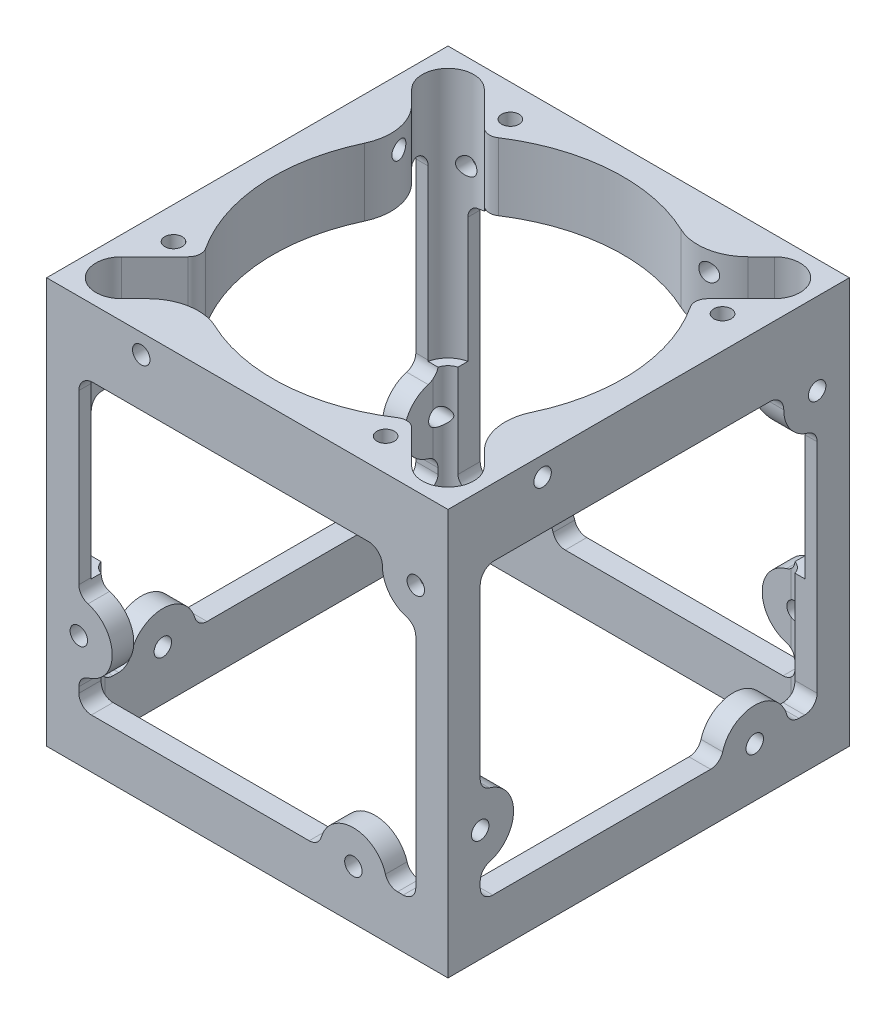
SolidWorks part; units mm, degrees
ref_plane "Front" through (0, 0, 0) normal (0, 0, 1) x (1, 0, 0)
ref_plane "Top" through (0, 0, 0) normal (0, 1, 0) x (1, 0, 0)
ref_plane "Right" through (0, 0, 0) normal (1, 0, 0) x (0, 0, -1)
other "Center of Mass"
sketch "Sketch1" plane through (0, 0, 0) normal (0, 1, 0) x (1, 0, 0)
  line L1 (-25.4, 25.4) -> (25.4, 25.4)
  line L2 (-25.4, 25.4) -> (-25.4, -25.4)
  line L3 (-25.4, -25.4) -> (25.4, -25.4)
  line L4 (25.4, 25.4) -> (25.4, -25.4)
  line L5 (-25.4, 25.4) -> (25.4, -25.4) construction
  line L6 (-25.4, -25.4) -> (25.4, 25.4) construction
  point P0 (0, 0)
  dimension "D1" = 50.8
  dimension "D2" = 50.8
extrude "Boss-Extrude1" add sketch "Sketch1" along normal blind 47.5488
sketch "Sketch2" plane through (0, 0, 0) normal (0, -1, 0) x (-1, 0, 0)
  line L1 (20.7645, -22.6695) -> (-20.7645, -22.6695)
  line L2 (22.6695, -20.7645) -> (22.6695, 20.7645)
  line L3 (20.7645, 22.6695) -> (-20.7645, 22.6695)
  line L4 (-22.6695, -20.7645) -> (-22.6695, 20.7645)
  line L5 (22.6695, -22.6695) -> (-22.6695, 22.6695) construction
  line L6 (22.6695, 22.6695) -> (-22.6695, -22.6695) construction
  arc A0 (-20.7645, 22.6695) -> (-22.6695, 20.7645) centre (-20.7645, 20.7645) ccw
  arc A1 (-22.6695, -20.7645) -> (-20.7645, -22.6695) centre (-20.7645, -20.7645) ccw
  arc A2 (20.7645, -22.6695) -> (22.6695, -20.7645) centre (20.7645, -20.7645) ccw
  arc A3 (20.7645, 22.6695) -> (22.6695, 20.7645) centre (20.7645, 20.7645) cw
  point P0 (0, 0)
  dimension "D3" = 1.905
  dimension "D1" = 45.339
  dimension "D2" = 45.339
extrude "Cut-Extrude1" cut sketch "Sketch2" against normal blind 33.02
sketch "Sketch4" plane through (0, 0, 0) normal (0, -1, 0) x (-1, 0, 0)
  line L0 (-22.1115, -22.1115) -> (-23.495, -23.495)
  line L3 (0, 0) -> (0, -4.5871)
  line L4 (-25.4, 0) -> (-22.6695, 0)
  line L5 (-25.4, -25.4) -> (-25.4, 25.4) construction
  line L6 (-22.6695, 20.7645) -> (-22.6695, -20.7645) construction
  line L8 (-23.495, -23.495) -> (23.495, -23.495)
  line L9 (-23.495, -23.495) -> (-23.495, 23.495)
  line L10 (-23.495, 23.495) -> (23.495, 23.495)
  line L11 (23.495, -23.495) -> (23.495, 23.495)
  line L12 (-23.495, -23.495) -> (23.495, 23.495) construction
  line L13 (-23.495, 23.495) -> (23.495, -23.495) construction
  arc A1 (-22.6695, -20.7645) -> (-20.7645, -22.6695) centre (-20.7645, -20.7645) ccw construction
  circle A2 centre (-23.495, -23.495) radius 1.1049
  circle A3 centre (23.495, -23.495) radius 1.1049
  circle A4 centre (-23.495, 23.495) radius 1.1049
  circle A5 centre (23.495, 23.495) radius 1.1049
  dimension "D2" = 2.2098
  dimension "D1" = 46.99
extrude "Cut-Extrude3" cut sketch "Sketch4" against normal blind 6.985 contours A3 | A5 | A4 | A2
sketch "Sketch5" plane through (0, 0, -25.4) normal (0, 0, -1) x (-1, 0, 0)
  line L0 (0, 0) -> (0, 47.5488)
  line L1 (-25.4, 0) -> (25.4, 0) construction
  line L2 (-25.4, 47.5488) -> (25.4, 47.5488) construction
  line L3 (0, 23.7744) -> (20.574, 23.7744)
  line L4 (0, 23.7744) -> (-20.574, 23.7744)
  line L5 (-23.7744, 47.5488) -> (23.7744, 47.5488)
  line L6 (-23.7744, 47.5488) -> (-23.7744, 0)
  line L7 (-23.7744, 0) -> (23.7744, 0)
  line L8 (23.7744, 47.5488) -> (23.7744, 0)
  line L9 (-23.7744, 47.5488) -> (23.7744, 0) construction
  line L10 (-23.7744, 0) -> (23.7744, 47.5488) construction
  circle A0 centre (-20.574, 23.7744) radius 0.5
  circle A1 centre (20.574, 23.7744) radius 0.5
  circle A2 centre (21.3233, 10.3505) radius 1.1049
  circle A3 centre (-13.4239, 2.4511) radius 1.1049
  circle A4 centre (-21.3233, 37.1983) radius 1.1049
  circle A5 centre (13.4239, 45.0977) radius 1.1049
  circle A6 centre (-21.3233, 10.3505) radius 1.1049
  circle A7 centre (-13.4239, 45.0977) radius 1.1049
  circle A8 centre (13.4239, 2.4511) radius 1.1049
  circle A9 centre (21.3233, 37.1983) radius 1.1049
  dimension "D1" = 1
  dimension "D2" = 1
  dimension "D3" = 2.2098
  dimension "D4" = 2.2098
  dimension "D5" = 2.2098
  dimension "D6" = 2.2098
  dimension "D7" = 20.574
  dimension "D8" = 20.574
extrude "Cut-Extrude5" cut sketch "Sketch5" against normal blind 6.985
sketch "Sketch6" plane through (-25.4, 0, 0) normal (-1, 0, 0) x (0, 0, 1)
  line L0 (0, 47.5488) -> (0, 0)
  line L1 (-25.4, 47.5488) -> (25.4, 47.5488) construction
  line L2 (-25.4, 0) -> (25.4, 0) construction
  line L3 (0, 0) -> (0, 47.5488)
  line L4 (0, 23.7744) -> (20.574, 23.7744)
  line L5 (0, 23.7744) -> (-20.574, 23.7744)
  line L6 (-23.7744, 47.5488) -> (23.7744, 47.5488)
  line L7 (-23.7744, 47.5488) -> (-23.7744, 0)
  line L8 (-23.7744, 0) -> (23.7744, 0)
  line L9 (23.7744, 47.5488) -> (23.7744, 0)
  line L10 (-23.7744, 47.5488) -> (23.7744, 0) construction
  line L11 (-23.7744, 0) -> (23.7744, 47.5488) construction
  circle A0 centre (-20.574, 23.7744) radius 0.5
  circle A1 centre (20.574, 23.7744) radius 0.5
  circle A2 centre (21.3233, 10.3505) radius 1.1049
  circle A3 centre (-13.4239, 2.4511) radius 1.1049
  circle A4 centre (-21.3233, 37.1983) radius 1.1049
  circle A5 centre (13.4239, 45.0977) radius 1.1049
  circle A6 centre (-21.3233, 10.3505) radius 1.1049
  circle A7 centre (-13.4239, 45.0977) radius 1.1049
  circle A8 centre (13.4239, 2.4511) radius 1.1049
  circle A9 centre (21.3233, 37.1983) radius 1.1049
  dimension "D1" = 1
  dimension "D2" = 2.2098
  dimension "D3" = 2.2098
  dimension "D4" = 20.574
  dimension "D5" = 20.574
extrude "Cut-Extrude6" cut sketch "Sketch6" against normal blind 6.985
sketch "Sketch7" plane through (0, 47.5488, 0) normal (0, 1, 0) x (1, 0, 0)
  line L0 (0, 25.4) -> (0, -25.4)
  line L1 (25.4, 25.4) -> (-25.4, 25.4) construction
  line L2 (-25.4, -25.4) -> (25.4, -25.4) construction
  line L3 (0, -23.7744) -> (0, 23.7744)
  line L4 (0, 0) -> (20.574, 0)
  line L5 (0, 0) -> (-20.574, 0)
  line L6 (-23.7744, 23.7744) -> (23.7744, 23.7744)
  line L7 (-23.7744, 23.7744) -> (-23.7744, -23.7744)
  line L8 (-23.7744, -23.7744) -> (23.7744, -23.7744)
  line L9 (23.7744, 23.7744) -> (23.7744, -23.7744)
  line L10 (-23.7744, 23.7744) -> (23.7744, -23.7744) construction
  line L11 (-23.7744, -23.7744) -> (23.7744, 23.7744) construction
  circle A0 centre (-20.574, 0) radius 0.5
  circle A1 centre (20.574, 0) radius 0.5
  circle A2 centre (21.3233, -13.4239) radius 1.1049
  circle A3 centre (-13.4239, -21.3233) radius 1.1049
  circle A4 centre (-21.3233, 13.4239) radius 1.1049
  circle A5 centre (13.4239, 21.3233) radius 1.1049
  circle A6 centre (-21.3233, -13.4239) radius 1.1049
  circle A7 centre (-13.4239, 21.3233) radius 1.1049
  circle A8 centre (13.4239, -21.3233) radius 1.1049
  circle A9 centre (21.3233, 13.4239) radius 1.1049
  dimension "D1" = 1
  dimension "D2" = 2.2098
  dimension "D3" = 2.2098
  dimension "D4" = 20.574
  dimension "D5" = 20.574
extrude "Cut-Extrude7" cut sketch "Sketch7" against normal blind 6.985
sketch "Sketch8" plane through (0, 0, 25.4) normal (0, 0, 1) x (1, 0, 0)
  line L0 (0, 47.5488) -> (0, 0)
  line L1 (-25.4, 47.5488) -> (25.4, 47.5488) construction
  line L2 (-25.4, 0) -> (25.4, 0) construction
  line L3 (0, 0) -> (0, 47.5488)
  line L4 (0, 23.7744) -> (20.574, 23.7744)
  line L5 (0, 23.7744) -> (-20.574, 23.7744)
  line L6 (-23.7744, 47.5488) -> (23.7744, 47.5488)
  line L7 (-23.7744, 47.5488) -> (-23.7744, 0)
  line L8 (-23.7744, 0) -> (23.7744, 0)
  line L9 (23.7744, 47.5488) -> (23.7744, 0)
  line L10 (-23.7744, 47.5488) -> (23.7744, 0) construction
  line L11 (-23.7744, 0) -> (23.7744, 47.5488) construction
  circle A0 centre (-20.574, 23.7744) radius 0.5
  circle A1 centre (20.574, 23.7744) radius 0.5
  circle A2 centre (21.3233, 10.3505) radius 1.1049
  circle A3 centre (-13.4239, 2.4511) radius 1.1049
  circle A4 centre (-21.3233, 37.1983) radius 1.1049
  circle A5 centre (13.4239, 45.0977) radius 1.1049
  circle A6 centre (-21.3233, 10.3505) radius 1.1049
  circle A7 centre (-13.4239, 45.0977) radius 1.1049
  circle A8 centre (13.4239, 2.4511) radius 1.1049
  circle A9 centre (21.3233, 37.1983) radius 1.1049
  dimension "D1" = 1
  dimension "D2" = 2.2098
  dimension "D3" = 2.2098
  dimension "D4" = 20.574
  dimension "D5" = 20.574
extrude "Cut-Extrude8" cut sketch "Sketch8" against normal blind 6.985 contours A6 | A7 | A9 | A8 | A1 | A0
sketch "Sketch9" plane through (25.4, 0, 0) normal (1, 0, 0) x (0, 0, -1)
  line L0 (0, 47.5488) -> (0, 0)
  line L1 (-25.4, 47.5488) -> (25.4, 47.5488) construction
  line L2 (-25.4, 0) -> (25.4, 0) construction
  line L3 (0, 0) -> (0, 47.5488)
  line L4 (0, 23.7744) -> (20.574, 23.7744)
  line L5 (0, 23.7744) -> (-20.574, 23.7744)
  line L6 (-23.7744, 47.5488) -> (23.7744, 47.5488)
  line L7 (-23.7744, 47.5488) -> (-23.7744, 0)
  line L8 (-23.7744, 0) -> (23.7744, 0)
  line L9 (23.7744, 47.5488) -> (23.7744, 0)
  line L10 (-23.7744, 47.5488) -> (23.7744, 0) construction
  line L11 (-23.7744, 0) -> (23.7744, 47.5488) construction
  circle A0 centre (-20.574, 23.7744) radius 0.5
  circle A1 centre (20.574, 23.7744) radius 0.5
  circle A2 centre (21.3233, 10.3505) radius 1.1049
  circle A3 centre (-13.4239, 2.4511) radius 1.1049
  circle A4 centre (-21.3233, 37.1983) radius 1.1049
  circle A5 centre (13.4239, 45.0977) radius 1.1049
  circle A6 centre (-21.3233, 10.3505) radius 1.1049
  circle A7 centre (-13.4239, 45.0977) radius 1.1049
  circle A8 centre (13.4239, 2.4511) radius 1.1049
  circle A9 centre (21.3233, 37.1983) radius 1.1049
  dimension "D1" = 1
  dimension "D2" = 2.2098
  dimension "D3" = 2.2098
  dimension "D4" = 20.574
  dimension "D5" = 20.574
extrude "Cut-Extrude9" cut sketch "Sketch9" against normal blind 6.985
sketch "Sketch10" plane through (-25.4, 0, 0) normal (-1, 0, 0) x (0, 0, 1)
  line L0 (0, 0) -> (0, 38.9989)
  line L1 (15.3201, 38.9989) -> (-19.5453, 38.9989)
  line L2 (0, 23.7744) -> (25.4, 23.7744)
  line L6 (25.4, 47.5488) -> (25.4, 0) construction
  line L8 (21.3233, 31.6065) -> (21.3233, 4.0386)
  line L9 (-25.4, 23.7744) -> (25.4, 23.7744)
  line L11 (19.7358, 2.4511) -> (19.0157, 2.4511)
  line L12 (7.8321, 2.4511) -> (-19.7358, 2.4511)
  line L13 (-21.3233, 11.4554) -> (-21.3233, 9.2456)
  line L14 (-21.3233, 4.0386) -> (-21.3233, 4.7587)
  line L15 (-21.3233, 15.9423) -> (-21.3233, 37.2209)
  line L19 (13.4239, 3.556) -> (13.4239, 1.3462)
  line L22 (0, 38.9989) -> (0, 0)
  arc A0 (17.098, 37.2142) -> (20.1694, 33.1336) centre (21.3233, 37.1983) ccw
  arc A1 (-20.1694, 6.2858) -> (-20.1694, 14.4152) centre (-21.3233, 10.3505) ccw
  arc A5 (20.1694, 33.1336) -> (21.3233, 31.6065) centre (19.7358, 31.6065) cw
  arc A6 (19.7358, 2.4511) -> (21.3233, 4.0386) centre (19.7358, 4.0386) ccw
  arc A7 (17.4886, 3.605) -> (9.3592, 3.605) centre (13.4239, 2.4511) ccw
  arc A8 (19.0157, 2.4511) -> (17.4886, 3.605) centre (19.0157, 4.0386) cw
  arc A9 (9.3592, 3.605) -> (7.8321, 2.4511) centre (7.8321, 4.0386) cw
  arc A10 (-19.7358, 2.4511) -> (-21.3233, 4.0386) centre (-19.7358, 4.0386) cw
  arc A11 (-21.3233, 4.7587) -> (-20.1694, 6.2858) centre (-19.7358, 4.7587) cw
  arc A12 (-20.1694, 14.4152) -> (-21.3233, 15.9423) centre (-19.7358, 15.9423) cw
  arc A18 (17.098, 37.2142) -> (15.3201, 38.9989) centre (15.3201, 37.2209) ccw
  arc A19 (-21.3233, 37.2209) -> (-19.5453, 38.9989) centre (-19.5453, 37.2209) cw
  dimension "D1" = 1.778
  dimension "D2" = 8.4506
  dimension "D3" = 8.4506
  dimension "D4" = 8.4506
extrude "Cut-Extrude10" cut sketch "Sketch10" against normal blind 10
sketch "Sketch11" plane through (0, 0, 25.4) normal (0, 0, 1) x (1, 0, 0)
  line L0 (15.3201, 38.9989) -> (-19.5453, 38.9989)
  line L1 (21.3233, 31.6065) -> (21.3233, 4.0386)
  line L3 (-25.4, 23.7744) -> (25.4, 23.7744)
  line L6 (-25.4, 47.5488) -> (-25.4, 0) construction
  line L7 (25.4, 47.5488) -> (25.4, 0) construction
  line L9 (19.7358, 2.4511) -> (19.0157, 2.4511)
  line L10 (7.8321, 2.4511) -> (-19.7358, 2.4511)
  line L11 (-21.3233, 11.4554) -> (-21.3233, 9.2456)
  line L12 (-21.3233, 4.0386) -> (-21.3233, 4.7587)
  line L13 (-21.3233, 15.9423) -> (-21.3233, 37.2209)
  line L18 (13.4239, 3.556) -> (13.4239, 1.3462)
  line L19 (0, 38.9989) -> (0, 0)
  circle A7 centre (-21.3233, 10.3505) radius 1.1049 construction
  arc A8 (17.098, 37.2142) -> (15.3201, 38.9989) centre (15.3201, 37.2209) ccw
  arc A12 (17.098, 37.2142) -> (20.1694, 33.1336) centre (21.3233, 37.1983) ccw
  arc A13 (-20.1694, 6.2858) -> (-20.1694, 14.4152) centre (-21.3233, 10.3505) ccw
  circle A18 centre (13.4239, 2.4511) radius 1.1049 construction
  arc A19 (20.1694, 33.1336) -> (21.3233, 31.6065) centre (19.7358, 31.6065) cw
  arc A20 (19.7358, 2.4511) -> (21.3233, 4.0386) centre (19.7358, 4.0386) ccw
  arc A21 (17.4886, 3.605) -> (9.3592, 3.605) centre (13.4239, 2.4511) ccw
  arc A22 (19.0157, 2.4511) -> (17.4886, 3.605) centre (19.0157, 4.0386) cw
  arc A23 (9.3592, 3.605) -> (7.8321, 2.4511) centre (7.8321, 4.0386) cw
  arc A24 (-19.7358, 2.4511) -> (-21.3233, 4.0386) centre (-19.7358, 4.0386) cw
  arc A25 (-21.3233, 4.7587) -> (-20.1694, 6.2858) centre (-19.7358, 4.7587) cw
  arc A26 (-20.1694, 14.4152) -> (-21.3233, 15.9423) centre (-19.7358, 15.9423) cw
  arc A32 (-21.3233, 37.2209) -> (-19.5453, 38.9989) centre (-19.5453, 37.2209) cw
  point P21 (0, 0)
  point P23 (0, 0)
  point P24 (0, 0)
  point P41 (21.3233, 32.973)
  point P46 (17.6492, 2.4511)
  point P49 (9.1986, 2.4511)
  point P54 (-21.3233, 6.1252)
  point P57 (-21.3233, 14.5758)
  dimension "D1" = 8.4506
  dimension "D3" = 1.778
  dimension "D9" = 8.4506
  dimension "D2" = 8.4506
extrude "Cut-Extrude11" cut sketch "Sketch11" against normal blind 8.89
sketch "Sketch13" plane through (0, 0, -25.4) normal (0, 0, -1) x (-1, 0, 0)
  line L0 (0, 0) -> (0, 38.9989)
  line L1 (15.3201, 38.9989) -> (-19.5453, 38.9989)
  line L2 (0, 23.7744) -> (6.3705, 23.7744)
  line L4 (21.3233, 31.6065) -> (21.3233, 4.0386)
  line L5 (-25.4, 23.7744) -> (25.4, 23.7744)
  line L7 (19.7358, 2.4511) -> (19.0157, 2.4511)
  line L8 (7.8321, 2.4511) -> (-19.7358, 2.4511)
  line L9 (-21.3233, 11.4554) -> (-21.3233, 9.2456)
  line L10 (-21.3233, 4.0386) -> (-21.3233, 4.7587)
  line L11 (-21.3233, 15.9423) -> (-21.3233, 37.2209)
  line L15 (13.4239, 3.556) -> (13.4239, 1.3462)
  line L18 (0, 38.9989) -> (0, 0)
  arc A0 (17.098, 37.2142) -> (20.1694, 33.1336) centre (21.3233, 37.1983) ccw
  arc A1 (-20.1694, 6.2858) -> (-20.1694, 14.4152) centre (-21.3233, 10.3505) ccw
  arc A5 (20.1694, 33.1336) -> (21.3233, 31.6065) centre (19.7358, 31.6065) cw
  arc A6 (19.7358, 2.4511) -> (21.3233, 4.0386) centre (19.7358, 4.0386) ccw
  arc A7 (17.4886, 3.605) -> (9.3592, 3.605) centre (13.4239, 2.4511) ccw
  arc A8 (19.0157, 2.4511) -> (17.4886, 3.605) centre (19.0157, 4.0386) cw
  arc A9 (9.3592, 3.605) -> (7.8321, 2.4511) centre (7.8321, 4.0386) cw
  arc A10 (-19.7358, 2.4511) -> (-21.3233, 4.0386) centre (-19.7358, 4.0386) cw
  arc A11 (-21.3233, 4.7587) -> (-20.1694, 6.2858) centre (-19.7358, 4.7587) cw
  arc A12 (-20.1694, 14.4152) -> (-21.3233, 15.9423) centre (-19.7358, 15.9423) cw
  arc A18 (17.098, 37.2142) -> (15.3201, 38.9989) centre (15.3201, 37.2209) ccw
  arc A19 (-21.3233, 37.2209) -> (-19.5453, 38.9989) centre (-19.5453, 37.2209) cw
  dimension "D1" = 1.778
  dimension "D2" = 8.4506
  dimension "D3" = 8.4506
  dimension "D4" = 8.4506
extrude "Cut-Extrude13" cut sketch "Sketch13" against normal blind 10
sketch "Sketch14" plane through (25.4, 0, 0) normal (1, 0, 0) x (0, 0, -1)
  line L1 (-25.4, 0) -> (25.4, 0) construction
  line L2 (15.3201, 38.9989) -> (-19.5453, 38.9989)
  line L3 (0, 23.7744) -> (6.7764, 23.7744)
  line L5 (21.3233, 31.6065) -> (21.3233, 4.0386)
  line L6 (-25.4, 23.7744) -> (25.4, 23.7744)
  line L8 (19.7358, 2.4511) -> (19.0157, 2.4511)
  line L9 (7.8321, 2.4511) -> (-19.7358, 2.4511)
  line L10 (-21.3233, 11.4554) -> (-21.3233, 9.2456)
  line L11 (-21.3233, 4.0386) -> (-21.3233, 4.7587)
  line L12 (-21.3233, 15.9423) -> (-21.3233, 37.2209)
  line L16 (13.4239, 3.556) -> (13.4239, 1.3462)
  line L19 (0, 38.9989) -> (0, 0)
  arc A0 (17.098, 37.2142) -> (20.1694, 33.1336) centre (21.3233, 37.1983) ccw
  arc A1 (-20.1694, 6.2858) -> (-20.1694, 14.4152) centre (-21.3233, 10.3505) ccw
  arc A5 (20.1694, 33.1336) -> (21.3233, 31.6065) centre (19.7358, 31.6065) cw
  arc A6 (19.7358, 2.4511) -> (21.3233, 4.0386) centre (19.7358, 4.0386) ccw
  arc A7 (17.4886, 3.605) -> (9.3592, 3.605) centre (13.4239, 2.4511) ccw
  arc A8 (19.0157, 2.4511) -> (17.4886, 3.605) centre (19.0157, 4.0386) cw
  arc A9 (9.3592, 3.605) -> (7.8321, 2.4511) centre (7.8321, 4.0386) cw
  arc A10 (-19.7358, 2.4511) -> (-21.3233, 4.0386) centre (-19.7358, 4.0386) cw
  arc A11 (-21.3233, 4.7587) -> (-20.1694, 6.2858) centre (-19.7358, 4.7587) cw
  arc A12 (-20.1694, 14.4152) -> (-21.3233, 15.9423) centre (-19.7358, 15.9423) cw
  arc A18 (-21.3233, 37.2209) -> (-19.5453, 38.9989) centre (-19.5453, 37.2209) cw
  arc A19 (15.3201, 38.9989) -> (17.098, 37.2142) centre (15.3201, 37.2209) cw
  dimension "D1" = 1.778
  dimension "D2" = 8.4506
  dimension "D3" = 8.4506
  dimension "D4" = 8.4506
extrude "Cut-Extrude14" cut sketch "Sketch14" against normal blind 10
sketch "Sketch15" plane through (0, 47.5488, 0) normal (0, 1, 0) x (1, 0, 0)
  line L0 (20.6546, -20.6546) -> (-20.6546, 20.6546)
  line L5 (20.6546, 20.6546) -> (-20.6546, -20.6546)
  line L8 (-20.6546, 20.6546) -> (20.6546, -20.6546) construction
  line L11 (-18.3556, 22.9535) -> (-14.1419, 18.7398)
  line L12 (-22.9535, 18.3556) -> (-21.2821, 16.6842)
  line L13 (20.6546, 20.6546) -> (-20.6546, -20.6546) construction
  line L14 (-16.6842, -21.2821) -> (-18.3556, -22.9535)
  line L15 (18.3556, 22.9535) -> (16.6842, 21.2821)
  line L16 (-22.9535, -18.3556) -> (-18.7398, -14.1419)
  line L17 (18.7398, 14.1419) -> (22.9535, 18.3556)
  line L18 (18.3556, -22.9535) -> (14.1419, -18.7398)
  line L19 (22.9535, -18.3556) -> (21.2821, -16.6842)
  arc A26 (-18.3556, 22.9535) -> (-22.9535, 18.3556) centre (-20.6546, 20.6546) ccw
  arc A27 (18.3556, -22.9535) -> (22.9535, -18.3556) centre (20.6546, -20.6546) ccw
  arc A28 (22.9535, 18.3556) -> (18.3556, 22.9535) centre (20.6546, 20.6546) ccw
  arc A29 (-22.9535, -18.3556) -> (-18.3556, -22.9535) centre (-20.6546, -20.6546) ccw
  arc A30 (9.4783, 20.0323) -> (-12.1491, 18.5346) centre (0, 0) ccw
  arc A31 (-9.4783, -20.0323) -> (12.1491, -18.5346) centre (0, 0) ccw
  arc A32 (20.0323, -9.4783) -> (18.5346, 12.1491) centre (0, 0) ccw
  arc A33 (-20.0323, 9.4783) -> (-18.5346, -12.1491) centre (0, 0) ccw
  arc A34 (-9.4783, -20.0323) -> (-16.6842, -21.2821) centre (-12.1941, -25.7723) ccw
  arc A35 (16.6842, 21.2821) -> (9.4783, 20.0323) centre (12.1941, 25.7723) cw
  arc A36 (-20.0323, 9.4783) -> (-21.2821, 16.6842) centre (-25.7723, 12.1941) ccw
  arc A37 (18.7398, 14.1419) -> (18.5346, 12.1491) centre (19.8623, 13.0194) ccw
  arc A38 (-12.1491, 18.5346) -> (-14.1419, 18.7398) centre (-13.0194, 19.8623) cw
  arc A39 (-18.7398, -14.1419) -> (-18.5346, -12.1491) centre (-19.8623, -13.0194) ccw
  arc A40 (12.1491, -18.5346) -> (14.1419, -18.7398) centre (13.0194, -19.8623) cw
  arc A41 (21.2821, -16.6842) -> (20.0323, -9.4783) centre (25.7723, -12.1941) cw
  point P3 (0, 0)
  point P7 (17.7999, 13.2021)
  point P13 (0, 0)
  point P17 (0, 0)
  point P27 (0, 0)
  point P34 (0, 0)
  point P39 (-17.7999, -13.2021)
  point P41 (0, 0)
  point P44 (13.2021, -17.7999)
  point P46 (0, 0)
  point P48 (17.7999, -13.2021)
  dimension "D1" = 22.1615
  dimension "D5" = 1.5875
  dimension "D6" = 6.35
  dimension "D2" = 6.5024
  dimension "D4" = 6.35
  dimension "D7" = 6.35
  dimension "D8" = 6.35
  dimension "D3" = 6.5024
extrude "Cut-Extrude15" cut sketch "Sketch15" against normal blind 31.75
sketch "Sketch16" plane through (0, 0, 0) normal (0, -1, 0) x (-1, 0, 0)
  line L0 (25.4, 25.4) -> (25.4, -25.4) construction
  line L1 (-25.4, -25.4) -> (25.4, -25.4)
  line L2 (-25.4, -25.4) -> (-25.4, 25.4)
  line L3 (-25.4, 25.4) -> (25.4, 25.4)
  line L4 (25.4, -25.4) -> (25.4, 25.4)
  line L5 (-25.4, -25.4) -> (25.4, 25.4) construction
  line L6 (-25.4, 25.4) -> (25.4, -25.4) construction
  line L8 (-20.7645, -22.6695) -> (20.7645, -22.6695)
  line L9 (-22.6695, -20.7645) -> (-22.6695, 20.7645)
  line L10 (-20.7645, 22.6695) -> (20.7645, 22.6695)
  line L11 (22.6695, -20.7645) -> (22.6695, 20.7645)
  line L12 (-22.6695, -22.6695) -> (22.6695, 22.6695) construction
  line L13 (-22.6695, 22.6695) -> (22.6695, -22.6695) construction
  arc A0 (22.6695, -20.7645) -> (20.7645, -22.6695) centre (20.7645, -20.7645) cw
  arc A1 (-22.6695, -20.7645) -> (-20.7645, -22.6695) centre (-20.7645, -20.7645) ccw
  arc A2 (20.7645, 22.6695) -> (22.6695, 20.7645) centre (20.7645, 20.7645) cw
  arc A3 (-20.7645, 22.6695) -> (-22.6695, 20.7645) centre (-20.7645, 20.7645) ccw
  circle A4 centre (-23.495, 23.495) radius 1.1049
  circle A5 centre (23.495, 23.495) radius 1.1049
  circle A6 centre (-23.495, -23.495) radius 1.1049
  circle A7 centre (23.495, -23.495) radius 1.1049
  point P0 (0, 0)
  point P8 (0, 0)
  dimension "D1" = 1.905
extrude "Boss-Extrude2" add sketch "Sketch16" along normal blind 3.81
